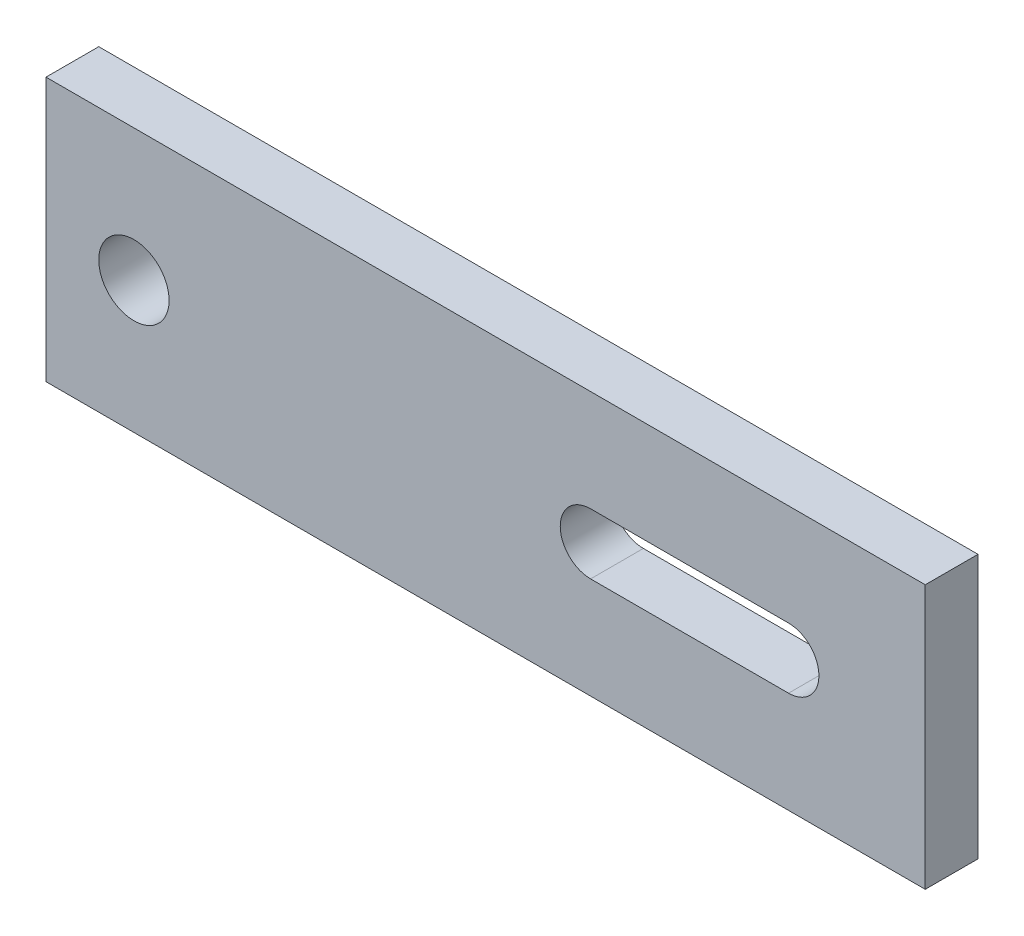
SolidWorks part; units mm, degrees
ref_plane "Front Plane" through (0, 0, 0) normal (0, 0, 1) x (1, 0, 0)
ref_plane "Top Plane" through (0, 0, 0) normal (0, 1, 0) x (1, 0, 0)
ref_plane "Right Plane" through (0, 0, 0) normal (1, 0, 0) x (0, 0, -1)
sketch "Sketch1" plane through (0, 0, 0) normal (0, 0, 1) x (1, 0, 0)
  line L1 (-25, 7.5) -> (25, 7.5)
  line L2 (-25, 7.5) -> (-25, -7.5)
  line L3 (-25, -7.5) -> (25, -7.5)
  line L4 (25, 7.5) -> (25, -7.5)
  line L5 (-25, 7.5) -> (25, -7.5) construction
  line L6 (-25, -7.5) -> (25, 7.5) construction
  point P0 (0, 0)
  dimension "D1" = 50
  dimension "D2" = 15
extrude "Boss-Extrude1" add sketch "Sketch1" along normal blind 3
sketch "Sketch2" plane through (0, 0, 3) normal (0, 0, 1) x (1, 0, 0)
  line L0 (-25, 7.5) -> (-25, -7.5) construction
  circle A0 centre (-20, 0) radius 2
  dimension "D1" = 4
  dimension "D2" = 5
extrude "Cut-Extrude1" cut sketch "Sketch2" against normal blind 3
sketch "Sketch3" plane through (0, 0, 3) normal (0, 0, 1) x (1, 0, 0)
  line L0 (5.9694, 0) -> (17.2263, 0) construction
  line L3 (5.9694, 1.7267) -> (17.2263, 1.7267)
  line L4 (5.9694, -1.7267) -> (17.2263, -1.7267)
  arc A3 (5.9694, 1.7267) -> (5.9694, -1.7267) centre (5.9694, 0) ccw
  arc A4 (17.2263, -1.7267) -> (17.2263, 1.7267) centre (17.2263, 0) ccw
  point P3 (11.5978, 0)
extrude "Cut-Extrude2" cut sketch "Sketch3" against normal blind 3
